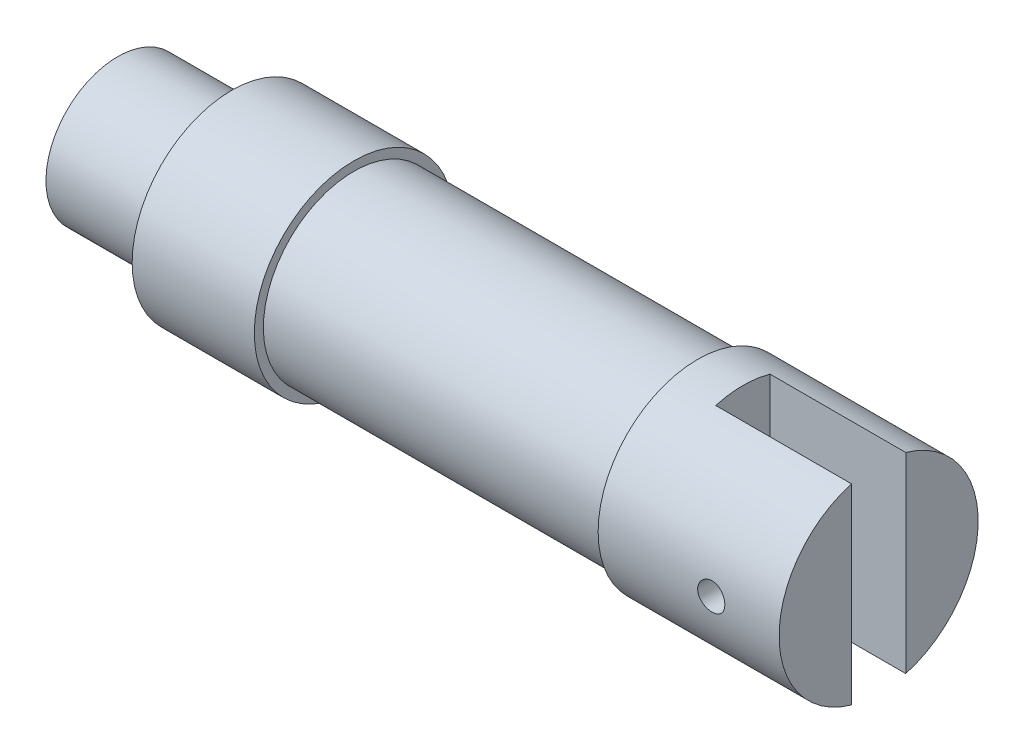
SolidWorks part; units mm, degrees
ref_plane "Plan de face" through (0, 0, 0) normal (0, 0, 1) x (1, 0, 0)
ref_plane "Plan de dessus" through (0, 0, 0) normal (0, 1, 0) x (1, 0, 0)
ref_plane "Plan de droite" through (0, 0, 0) normal (1, 0, 0) x (0, 0, -1)
sketch "Esquisse1" plane through (0, 0, 0) normal (0, 0, 1) x (1, 0, 0)
  line L0 (40, 0) -> (168.2, 0) construction
  line L2 (40, 3) -> (0, 3)
  line L3 (0, 3) -> (0, 15.85)
  line L4 (0, 15.85) -> (25.2, 15.85)
  line L5 (25.2, 15.85) -> (25.2, 22)
  line L6 (25.2, 22) -> (52.2, 22)
  line L7 (52.2, 22) -> (52.2, 20)
  line L8 (52.2, 20) -> (128.2, 20)
  line L9 (128.2, 20) -> (128.2, 22)
  line L10 (128.2, 22) -> (168.2, 22)
  line L11 (168.2, 22) -> (168.2, 0)
  line L12 (40, 3) -> (40, 0)
  line L14 (40, 0) -> (168.2, 0)
  dimension "D1" = 44
  dimension "D2" = 40
  dimension "D3" = 40
  dimension "D4" = 31.7
  dimension "D5" = 6
  dimension "D6" = 76
  dimension "D7" = 40
  dimension "D8" = 25.2
  dimension "D9" = 27
revolve "Révolution1" add sketch "Esquisse1" angle 360 about L0
sketch "Esquisse2" plane through (0, 0, 0) normal (0, 1, 0) x (1, 0, 0)
  line L0 (168.2, -22) -> (168.2, 22) construction
  line L1 (168.2, 6) -> (138.2, 6)
  line L2 (168.2, 6) -> (168.2, -6)
  line L3 (168.2, -6) -> (138.2, -6)
  line L4 (138.2, 6) -> (138.2, -6)
  line L5 (0, 0) -> (168.2, 0) construction
  dimension "D1" = 12
  dimension "D2" = 6
  dimension "D3" = 30
extrude "Enlèv. mat.-Extru.1" cut sketch "Esquisse2" against normal through all and the other way through all
sketch "Esquisse3" plane through (0, 0, -6) normal (0, 0, 1) x (1, 0, 0)
  line L0 (153.2, 21.166) -> (153.2, -21.166) construction
  line L1 (168.2, 21.166) -> (138.2, 21.166) construction
  line L2 (138.2, -21.166) -> (168.2, -21.166) construction
  line L3 (168.2, 0) -> (128.2, 0) construction
  line L4 (168.2, -21.166) -> (168.2, 21.166) construction
  line L5 (128.2, 20) -> (128.2, -20) construction
  circle A0 centre (153.2, 0) radius 3
  dimension "D1" = 6
extrude "Enlèv. mat.-Extru.2" cut sketch "Esquisse3" against normal through all and the other way through all
